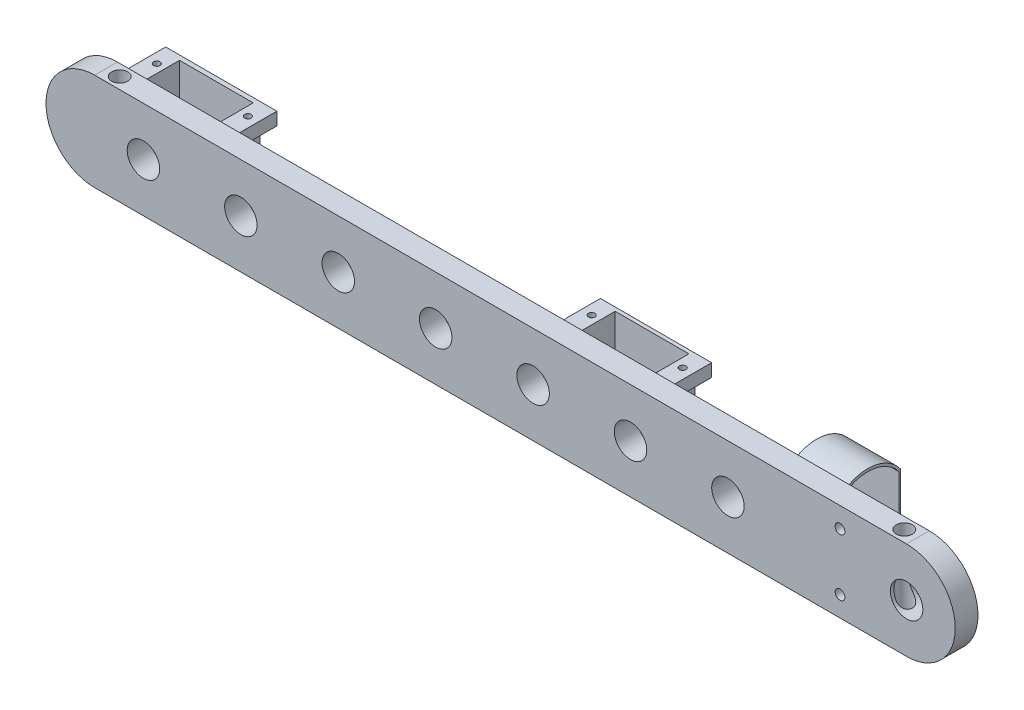
SolidWorks part; units mm, degrees
ref_plane "Front Plane" through (0, 0, 0) normal (0, 0, 1) x (1, 0, 0)
ref_plane "Top Plane" through (0, 0, 0) normal (0, 1, 0) x (1, 0, 0)
ref_plane "Right Plane" through (0, 0, 0) normal (1, 0, 0) x (0, 0, -1)
sketch "Sketch1" plane through (0, 0, 0) normal (0, 0, 1) x (1, 0, 0)
  line L0 (-200, 0) -> (50, 0)
  line L1 (50, -30) -> (-200, -30)
  arc A0 (50, 0) -> (50, -30) centre (50, -15) cw
  arc A1 (-200, -30) -> (-200, 0) centre (-200, -15) cw
  point P7 (-75, 0)
  dimension "D3" = 50
  dimension "D1" = 125
  dimension "D2" = 30
extrude "Boss-Extrude1" add sketch "Sketch1" along normal blind 7
sketch "Sketch2" plane through (0, 0, 7) normal (0, 0, 1) x (1, 0, 0)
  line L2 (50, 0) -> (-200, 0) construction
  circle A0 centre (-185, -15) radius 5
  arc A6 (-200, 0) -> (-200, -30) centre (-200, -15) ccw construction
  point P22 (-215, -15)
  dimension "D1" = 10
  dimension "D3" = 15
  dimension "D2" = 30
extrude "Cut-Extrude1" cut sketch "Sketch2" against normal blind 7
sketch "Sketch5" plane through (0, 0, 0) normal (0, 1, 0) x (1, 0, 0)
  line L1 (-318.748, 64.8797) -> (45.4135, 64.8797) construction
  line L2 (-318.748, 64.8797) -> (-318.748, -30.5338) construction
  line L3 (-318.748, -30.5338) -> (45.4135, -30.5338) construction
  line L4 (45.4135, 64.8797) -> (45.4135, -30.5338) construction
  line L5 (-318.748, 64.8797) -> (45.4135, -30.5338) construction
  line L6 (-318.748, -30.5338) -> (45.4135, 64.8797) construction
  point P0 (-136.6672, 17.1729)
pattern_linear "LPattern1" count 7 spacing 30 along (1, 0, 0) of "Cut-Extrude1"
sketch "Sketch6" plane through (0, 0, 0) normal (0, 0, -1) x (-1, 0, 0)
  circle A0 centre (-50, -15) radius 5
  dimension "D1" = 10
extrude "Cut-Extrude2" cut sketch "Sketch6" against normal blind 10
sketch "Sketch7" plane through (0, 0, 0) normal (1, 0, 0) x (0, 0, -1)
  line L0 (20.1244, -8.0466) -> (20.1244, -21.3918)
  line L1 (0, -8.0466) -> (0, -21.3918)
  line L2 (0, -30) -> (0, 0) construction
  arc A0 (20.1244, -21.3918) -> (0, -21.3918) centre (10.0622, -13.1301) cw
  arc A1 (20.1244, -8.0466) -> (0, -8.0466) centre (10.0622, -15.3827) ccw
  dimension "D3" = 12.4526
  dimension "D4" = 13.0194
  dimension "D1" = 13.3452
  dimension "D2" = 20.1244
extrude "Boss-Extrude2" add sketch "Sketch7" along normal blind 21
sketch "Sketch8" plane through (21, 0, 0) normal (1, 0, 0) x (0, 0, -1)
  line L0 (0.3437, -8.6037) -> (0.3437, -21.0037)
  line L1 (0.3437, -21.0037) -> (3.2516, -23.3301)
  line L2 (3.2516, -23.3301) -> (6.1148, -24.6722)
  line L3 (6.1148, -24.6722) -> (10.1412, -25.388)
  line L4 (10.1412, -25.388) -> (14.1229, -24.6722)
  line L5 (14.1229, -24.6722) -> (17.1651, -23.3301)
  line L6 (17.1651, -23.3301) -> (19.6704, -20.9533)
  line L7 (19.6704, -20.9533) -> (19.6704, -8.5533)
  arc A0 (0.3437, -8.6037) -> (19.6704, -8.5533) centre (10.0259, -15.8054) cw
  dimension "D1" = 12.4
extrude "Cut-Extrude3" cut sketch "Sketch8" against normal blind 21
sketch "Sketch9" plane through (0, 0, 0) normal (0, 0, -1) x (-1, 0, 0)
  line L0 (-50, -15) -> (-29.5, -15)
  line L1 (-29.5, -6.25) -> (-29.5, -23.75)
  circle A0 centre (-29.5, -6.25) radius 1.5
  circle A1 centre (-29.5, -23.75) radius 1.5
  point P6 (-29.5, -15)
  dimension "D3" = 3
  dimension "D4" = 3
  dimension "D1" = 20.5
  dimension "D2" = 17.5
extrude "Cut-Extrude4" cut sketch "Sketch9" against normal up to next contours A1 | A0
sketch "Sketch10" plane through (0, 0, -20.1244) normal (0, 0, -1) x (-1, 0, 0)
  line L0 (-21, -26.1494) -> (0, -26.1494) construction
  line L1 (0, -2.9301) -> (-5.2715, -2.9301)
  line L2 (0, -2.9301) -> (0, -26.1494)
  line L3 (0, -26.1494) -> (-5.2715, -26.1494)
  line L4 (-5.2715, -2.9301) -> (-5.2715, -26.1494)
  dimension "D1" = 5.2715
extrude "Cut-Extrude5" cut sketch "Sketch10" against normal up to surface (20.1244 mm away) up to face at (28, -23.75, 0)
sketch "Sketch11" plane through (0, 0, 0) normal (0, 0, -1) x (-1, 0, 0)
  line L0 (60.0976, -6.42) -> (60.0976, -23.9134)
  line L1 (60.0976, -23.9134) -> (36.2199, -23.9134)
  line L2 (36.2199, -23.9134) -> (36.2199, -6.6133)
  line L3 (36.2199, -6.6133) -> (31.0205, -6.6133)
  line L4 (31.0205, -6.6133) -> (31.0205, -2.6749)
  line L5 (31.0205, -2.6749) -> (65.2766, -2.6749)
  line L6 (65.2766, -2.6749) -> (65.2766, -6.42)
  line L7 (65.2766, -6.42) -> (60.0976, -6.42)
  line L8 (200, -30) -> (-50, -30) construction
  line L9 (-50, 0) -> (200, 0) construction
  line L10 (-5.2715, -21.3918) -> (-5.2715, -8.0466) construction
  line L11 (-5.2715, -21.0037) -> (-5.2715, -8.6037) construction
  line L12 (193.9754, -6.286) -> (193.9754, -16.5408)
  line L13 (193.9754, -16.5408) -> (170.0976, -16.5408)
  line L14 (170.0976, -16.5408) -> (170.0976, -6.4792)
  line L15 (170.0976, -6.4792) -> (164.8982, -6.4792)
  line L16 (164.8982, -6.4792) -> (164.8982, -2.5408)
  line L17 (164.8982, -2.5408) -> (199.1543, -2.5408)
  line L18 (199.1543, -2.5408) -> (199.1543, -6.286)
  line L19 (199.1543, -6.286) -> (193.9754, -6.286)
  circle A0 centre (65, -15) radius 5 construction
  point P26 (65.2766, -4.5474)
  dimension "D1" = 34.2561
  dimension "D2" = 6.0866
  dimension "D3" = 2.6749
  dimension "D4" = 41.4915
  dimension "D5" = 4.9024
  dimension "D6" = 3.7451
  dimension "D7" = 3.9384
  dimension "D8" = 36.292
  dimension "D9" = 34.2561
  dimension "D10" = 3.7451
  dimension "D11" = 110
  dimension "D12" = 2.5408
  dimension "D13" = 23.8777
  dimension "D14" = 14
  dimension "D15" = 99.6216
  dimension "D16" = 6.4792
extrude "Boss-Extrude3" add sketch "Sketch11" along normal blind 14
sketch "Sketch12" plane through (0, -2.6749, 0) normal (0, 1, 0) x (1, 0, 0)
  line L0 (-65.2766, 14) -> (-65.2766, 0) construction
  line L1 (-59.5766, 12.8538) -> (-36.8766, 12.8538)
  line L2 (-59.5766, 12.8538) -> (-59.5766, 0.5538)
  line L3 (-59.5766, 0.5538) -> (-36.8766, 0.5538)
  line L4 (-36.8766, 12.8538) -> (-36.8766, 0.5538)
  line L5 (-193.4543, 12.5731) -> (-170.7543, 12.5731)
  line L6 (-193.4543, 12.5731) -> (-193.4543, 0.2731)
  line L7 (-193.4543, 0.2731) -> (-170.7543, 0.2731)
  line L8 (-170.7543, 12.5731) -> (-170.7543, 0.2731)
  line L9 (-199.1543, 14) -> (-199.1543, 0) construction
  line L10 (-61.9264, 21.0679) -> (-39.5264, 21.0679)
  line L11 (-61.9264, 21.0679) -> (-61.9264, 33.1679)
  line L12 (-61.9264, 33.1679) -> (-39.5264, 33.1679)
  line L13 (-39.5264, 21.0679) -> (-39.5264, 33.1679)
  dimension "D1" = 5.7
  dimension "D2" = 5.7
  dimension "D3" = 12.1
  dimension "D4" = 22.4
  dimension "D5" = 12.3
  dimension "D6" = 22.7
  dimension "D7" = 22.7
  dimension "D8" = 12.3
extrude "Cut-Extrude6" cut sketch "Sketch12" against normal blind 22 and the other way blind 1 contours L4 L1 L2 L3 | L8 L5 L6 L7
sketch "Sketch13" plane through (0, -2.6749, 0) normal (0, 1, 0) x (1, 0, 0)
  line L0 (-199.1543, 14) -> (-199.1543, 0) construction
  line L1 (-199.1543, 14) -> (-164.8982, 14) construction
  line L2 (-61.1766, 7.0028) -> (-61.1766, 2.942) construction
  line L3 (-65.2766, 14) -> (-65.2766, 0) construction
  line L4 (-35.1205, 8.19) -> (-35.1205, 7.609) construction
  line L5 (-35.1205, 7.609) -> (-35.1205, 2.942) construction
  line L6 (-31.0205, 14) -> (-31.0205, 0) construction
  line L7 (-65.2766, 14) -> (-31.0205, 14) construction
  line L8 (-195.0543, 8.5238) -> (-195.0543, 4.463) construction
  line L9 (-164.8982, 14) -> (-164.8982, 0) construction
  line L10 (-168.9982, 8.19) -> (-168.9982, 7.609) construction
  line L11 (-168.9982, 7.609) -> (-168.9982, 2.942) construction
  circle A0 centre (-62.1766, 8.19) radius 1
  circle A1 centre (-34.1205, 8.19) radius 1
  circle A2 centre (-196.0543, 8.19) radius 1
  circle A3 centre (-167.9982, 8.19) radius 1
  point P28 (-199.1543, 7)
  dimension "D1" = 2
  dimension "D2" = 2
  dimension "D4" = 4.1
  dimension "D8" = 2
  dimension "D9" = 2
  dimension "D3" = 5.81
  dimension "D5" = 4.1
  dimension "D6" = 4.1
  dimension "D7" = 5.81
  dimension "D10" = 4.1
extrude "Cut-Extrude7" cut sketch "Sketch13" against normal blind 7 and the other way blind 7 contours A3 | A2 | A0 | A1
sketch "Sketch14" plane through (-36.2199, 0, 0) normal (1, 0, 0) x (0, 0, -1)
  line L0 (14, -6.6133) -> (14, -23.9134) construction
  line L1 (14, -13.9134) -> (2, -13.9134)
  line L2 (14, -13.9134) -> (14, -23.9134)
  line L3 (14, -23.9134) -> (2, -23.9134)
  line L4 (2, -13.9134) -> (2, -23.9134)
  line L5 (14, -23.9134) -> (0, -23.9134) construction
  dimension "D1" = 0
  dimension "D2" = 12
  dimension "D3" = 10
  dimension "D4" = 0
extrude "Cut-Extrude8" cut sketch "Sketch14" against normal up to surface (157.7554 mm away) up to face at (-193.9754, -11.4134, -7)
sketch "Sketch15" plane through (0, 0, 0) normal (0, 1, 0) x (1, 0, 0)
  line L0 (-200, -7) -> (-200, 0) construction
  line L1 (50, -7) -> (50, 0) construction
  circle A0 centre (-195.8, -3.5) radius 2.5
  circle A1 centre (45.8, -3.5) radius 2.5
  point P7 (-200, -3.5)
  point P12 (50, -3.5)
  dimension "D2" = 5
  dimension "D3" = 5
  dimension "D1" = 4.2
  dimension "D4" = 4.2
extrude "Cut-Extrude9" cut sketch "Sketch15" against normal up to next
